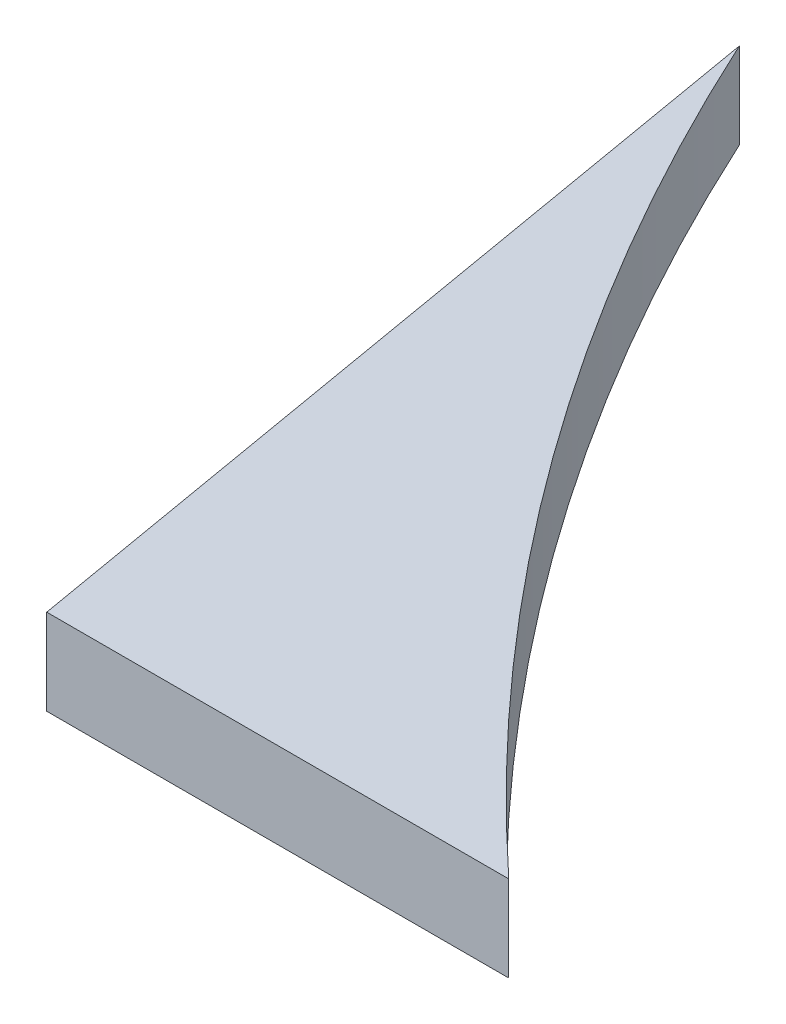
SolidWorks part; units mm, degrees
ref_plane "前视基准面" through (0, 0, 0) normal (0, 0, 1) x (1, 0, 0)
ref_plane "上视基准面" through (0, 0, 0) normal (0, 1, 0) x (1, 0, 0)
ref_plane "右视基准面" through (0, 0, 0) normal (1, 0, 0) x (0, 0, -1)
other "Configuration Table"
sketch "草图1" plane through (0, 0, 0) normal (0, 1, 0) x (1, 0, 0)
  line L0 (-13.2748, -82.8278) -> (-27.3224, -82.8278)
  line L1 (27.3224, -82.8278) -> (13.2748, -82.8278)
  line L2 (39.0308, -14.8139) -> (27.3224, -82.8278)
  line L3 (-21.5, -14.8139) -> (39.0308, -14.8139)
  line L4 (-21.5, -14.8139) -> (-21.5, -20.4375)
  line L5 (-21.5, -20.4375) -> (-38.0627, -20.4375)
  line L6 (-27.3224, -82.8278) -> (-38.0627, -20.4375)
  arc A0 (13.2748, -82.8278) -> (-13.2748, -82.8278) centre (0, -59.1141) ccw
sketch "草图2" plane through (0, 0, 0) normal (0, 1, 0) x (1, 0, 0)
  line L6 (-13.2748, -81.8278) -> (-26.4798, -81.8278)
  line L7 (-26.4798, -81.8278) -> (-37.0772, -20.2679)
  line L8 (-21.0971, -81.8278) -> (-26.4798, -81.8278)
  line L9 (-26.4798, -81.8278) -> (-28.1577, -72.0811)
  circle A2 centre (0, -59.1141) radius 30 construction
  arc A4 (-28.1577, -72.0811) -> (-21.0971, -81.8278) centre (0, -59.1141) ccw
  point P6 (0, 0)
  point P7 (-21.0971, -81.8278)
  dimension "D2" = 1
  dimension "D1" = 60
  dimension "D3" = 1
extrude "凸台-拉伸1" add sketch "草图2" along normal blind 1 contours A4 L9 L8
